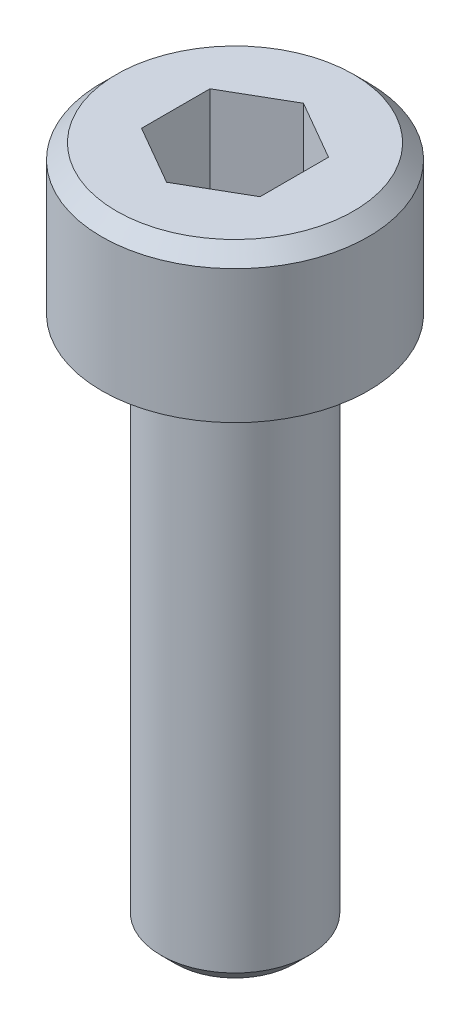
SolidWorks part; units mm, degrees
ref_plane "Front Plane" through (0, 0, 0) normal (0, 0, 1) x (1, 0, 0)
ref_plane "Top Plane" through (0, 0, 0) normal (0, 1, 0) x (1, 0, 0)
ref_plane "Right Plane" through (0, 0, 0) normal (1, 0, 0) x (0, 0, -1)
sketch "Sketch1" plane through (0, 0, 0) normal (0, 0, 1) x (1, 0, 0)
  line L0 (0, 14.9185) -> (0, -14.3315) construction
  line L1 (0, 11.5) -> (4.5, 11.5)
  line L2 (4.5, 11.5) -> (4.5, 6.5)
  line L3 (4.5, 6.5) -> (2.5, 6.5)
  line L4 (2.5, 6.5) -> (2.5, -11.5)
  line L5 (2.5, -11.5) -> (0, -11.5)
  line L6 (0, 11.5) -> (0, -11.5)
  dimension "D1" = 18
  dimension "D2" = 5
  dimension "D3" = 2.5
  dimension "D4" = 11.5
  dimension "D5" = 4.5
revolve "Revolve1" add sketch "Sketch1" angle 360 about L0
sketch "Sketch2" plane through (0, 11.5, 0) normal (0, 1, 0) x (1, 0, 0)
  line L0 (0, 4.5) -> (0, -4.5) construction
  line L1 (0, 2.3094) -> (-2, 1.1547)
  line L2 (-2, 1.1547) -> (-2, -1.1547)
  line L3 (-2, -1.1547) -> (0, -2.3094)
  line L4 (0, -2.3094) -> (2, -1.1547)
  line L5 (2, -1.1547) -> (2, 1.1547)
  line L6 (2, 1.1547) -> (0, 2.3094)
  circle A0 centre (0, 0) radius 2 construction
  circle A1 centre (0, 0) radius 4.5 construction
  dimension "D1" = 4
extrude "Cut-Extrude1" cut sketch "Sketch2" against normal blind 4
chamfer "Chamfer1" distance 0.5 angle 45 1 edges at (0, 11.5, 4.5)
chamfer "Chamfer2" distance 0.5 angle 45 1 edges at (0, -11.5, 2.5)
